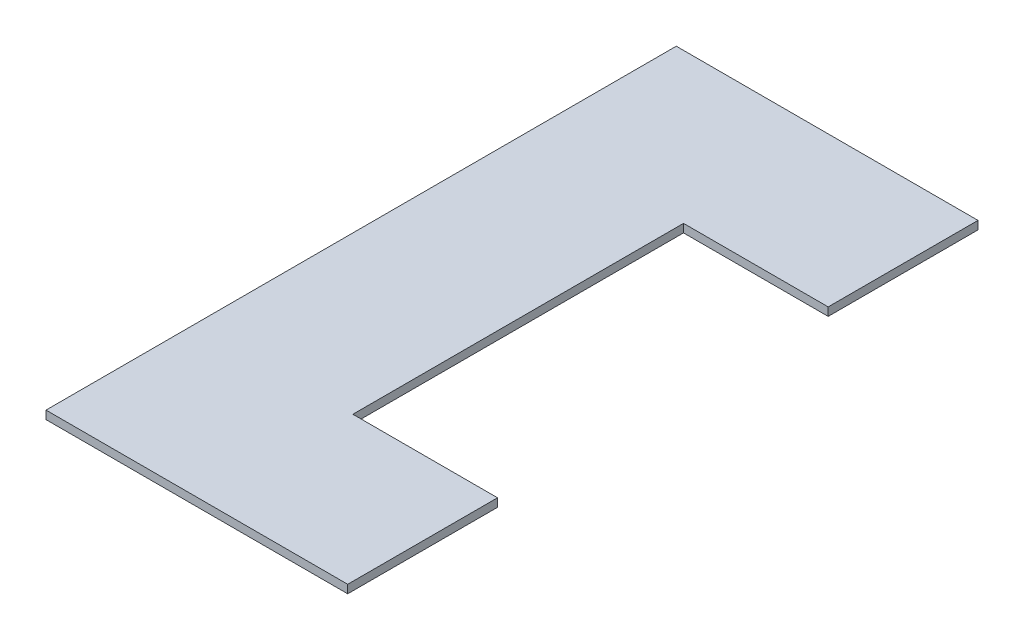
SolidWorks part; units mm, degrees
ref_plane "Alzado" through (0, 0, 0) normal (0, 0, 1) x (1, 0, 0)
ref_plane "Planta" through (0, 0, 0) normal (0, 1, 0) x (1, 0, 0)
ref_plane "Vista lateral" through (0, 0, 0) normal (1, 0, 0) x (0, 0, -1)
sketch "Croquis1" plane through (0, 0, 0) normal (0, 1, 0) x (1, 0, 0)
  line L0 (-100, 155) -> (-50, 155)
  line L1 (-200, 155) -> (200, 155) construction
  line L2 (-200, 155) -> (-200, -155) construction
  line L3 (-200, -155) -> (200, -155) construction
  line L4 (200, 155) -> (200, -155) construction
  line L5 (-200, 155) -> (200, -155) construction
  line L6 (-200, -155) -> (200, 155) construction
  line L7 (-200, -155) -> (-150, -155)
  line L8 (-200, -155) -> (-200, 155)
  line L9 (-200, 155) -> (-150, 155)
  line L10 (-50, -155) -> (-50, 155)
  line L11 (-150, -151) -> (-100, -151) construction
  line L12 (-150, -151) -> (-150, -155) construction
  line L13 (-150, -155) -> (-100, -155) construction
  line L14 (-100, -151) -> (-100, -155) construction
  line L15 (-150, 151) -> (-100, 151) construction
  line L16 (-150, 151) -> (-150, 155) construction
  line L17 (-150, 155) -> (-100, 155) construction
  line L18 (-100, 151) -> (-100, 155) construction
  line L19 (-150, 151) -> (-100, 155) construction
  line L20 (-150, 155) -> (-100, 151) construction
  line L21 (-200, 105) -> (-196, 105) construction
  line L22 (-200, 105) -> (-200, 55) construction
  line L23 (-200, 55) -> (-196, 55) construction
  line L24 (-196, 105) -> (-196, 55) construction
  line L25 (-200, 105) -> (-196, 55) construction
  line L26 (-200, 55) -> (-196, 105) construction
  line L27 (-200, -55) -> (-196, -55) construction
  line L28 (-200, -55) -> (-200, -105) construction
  line L29 (-200, -105) -> (-196, -105) construction
  line L30 (-196, -55) -> (-196, -105) construction
  line L31 (-200, -55) -> (-196, -105) construction
  line L32 (-200, -105) -> (-196, -55) construction
  line L33 (-100, -155) -> (-50, -155)
  line L34 (-196, 155) -> (-196, -155)
  line L35 (-150, 155) -> (-100, 155)
  line L36 (-150, -155) -> (-100, -155)
  point P0 (0, 0)
  point P16 (-125, 153)
  point P21 (-198, 80)
  point P26 (-198, -80)
  point P30 (-196, -105)
  dimension "D1" = 310
  dimension "D2" = 400
  dimension "D3" = 150
  dimension "D4" = 50
  dimension "D5" = 50
  dimension "D6" = 50
  dimension "D7" = 50
  dimension "D8" = 50
  dimension "D9" = 4
extrude "Saliente-Extruir1" add sketch "Croquis1" along normal blind 4 contours L9 L34 L7 L12 L11 L14 L33 L10 L0 L18 L15 L16
sketch "Croquis2" plane through (0, 4, 0) normal (0, 1, 0) x (1, 0, 0)
  line L30 (-50, -155) -> (-50, 155) construction
  line L31 (-196, 155) -> (-50, 155)
  line L32 (-196, 155) -> (-196, 152.5)
  line L33 (-196, 152.5) -> (-50, 152.5)
  line L34 (-50, 155) -> (-50, 152.5)
  line L35 (-196, 155) -> (-50, 152.5) construction
  line L36 (-196, 152.5) -> (-50, 155) construction
  line L38 (-196, -155) -> (-50, -155)
  line L39 (-196, -155) -> (-196, -152.5)
  line L40 (-196, -152.5) -> (-50, -152.5)
  line L41 (-50, -155) -> (-50, -152.5)
  line L42 (-196, -155) -> (-50, -152.5) construction
  line L43 (-196, -152.5) -> (-50, -155) construction
  point P5 (-123, 153.75)
  point P12 (-123, -153.75)
  dimension "D1" = 2.5
extrude "Cortar-Extruir1" cut sketch "Croquis2" against normal blind 10
sketch "Croquis3" plane through (0, 4, 0) normal (0, 1, 0) x (1, 0, 0)
  line L0 (-50, -152.5) -> (-50, 152.5) construction
  line L1 (-120, 80) -> (-50, 80)
  line L2 (-120, 80) -> (-120, -80)
  line L3 (-120, -80) -> (-50, -80)
  line L4 (-50, 80) -> (-50, -80)
  line L5 (-120, 80) -> (-50, -80) construction
  line L6 (-120, -80) -> (-50, 80) construction
  point P0 (-85, 0)
  dimension "D1" = 160
  dimension "D2" = 70
extrude "Cortar-Extruir2" cut sketch "Croquis3" against normal blind 10
equation "\"D2@Croquis1\" = \"largo_tot\""
equation "\"D3@Croquis1\"=150"
equation "\"D1@Croquis1\" = \"ancho_tot\""
equation "\"venesta\"= 4'grosor de la venesta"
equation "\"policarbonato\"= 4'grosor del policarbonato"
equation "\"carton_trupan\"= 3'grosor del carton trupan caso laser"
equation "\"ancho_tot\"= 310'ancho tot sin llantas"
equation "\"largo_tot\"= 400'largo tot sin camera"
equation "\"D1@Saliente-Extruir1\"=\"policarbonato\""
equation "\"D9@Croquis1\"=\"policarbonato\""
